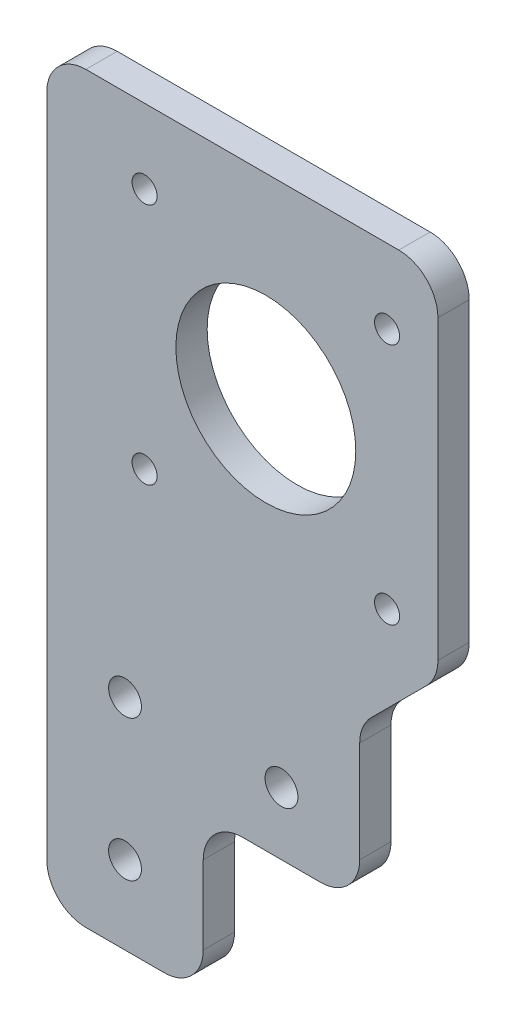
SolidWorks part; units mm, degrees
ref_plane "Спереди" through (0, 0, 0) normal (0, 0, 1) x (1, 0, 0)
ref_plane "Сверху" through (0, 0, 0) normal (0, 1, 0) x (1, 0, 0)
ref_plane "Справа" through (0, 0, 0) normal (1, 0, 0) x (0, 0, -1)
sketch "Model" plane through (0, 0, 0) normal (0, 0, 1) x (1, 0, 0)
  line L69 (274.0282, 189.1642) -> (274.0282, 151.2354)
  line L70 (272.5637, 147.6998) -> (265.4927, 140.6288)
  line L71 (264.0282, 137.0932) -> (264.0282, 124.1643)
  line L72 (259.0282, 119.1644) -> (249.0282, 119.1644)
  line L73 (244.0283, 114.1644) -> (244.0283, 104.1644)
  line L74 (239.0283, 99.1644) -> (229.0283, 99.1644)
  line L75 (224.0283, 104.1644) -> (224.0283, 189.1642)
  line L76 (229.0283, 194.1642) -> (269.0282, 194.1642)
  circle A41 centre (267.5282, 184.6642) radius 1.6
  circle A42 centre (267.5282, 153.6643) radius 1.6
  circle A43 centre (236.5283, 153.6643) radius 1.6
  circle A44 centre (236.5283, 184.6642) radius 1.6
  circle A45 centre (254.0282, 127.1643) radius 2.1
  circle A46 centre (234.0283, 127.1643) radius 2.1
  circle A47 centre (234.0283, 109.1644) radius 2.1
  circle A48 centre (252.0282, 169.1643) radius 11.5
  arc A150 (272.5637, 147.6998) -> (274.0282, 151.2354) centre (269.0282, 151.2354) ccw
  arc A151 (265.4927, 140.6288) -> (264.0282, 137.0932) centre (269.0282, 137.0932) ccw
  arc A152 (259.0282, 119.1644) -> (264.0282, 124.1643) centre (259.0282, 124.1643) ccw
  arc A153 (249.0282, 119.1644) -> (244.0283, 114.1644) centre (249.0282, 114.1644) ccw
  arc A154 (239.0283, 99.1644) -> (244.0283, 104.1644) centre (239.0283, 104.1644) ccw
  arc A155 (224.0283, 104.1644) -> (229.0283, 99.1644) centre (229.0283, 104.1644) ccw
  arc A156 (229.0283, 194.1642) -> (224.0283, 189.1642) centre (229.0283, 189.1642) ccw
  arc A157 (274.0282, 189.1642) -> (269.0282, 194.1642) centre (269.0282, 189.1642) ccw
extrude "Бобышка-Вытянуть1" add sketch "Model" along normal blind 4
